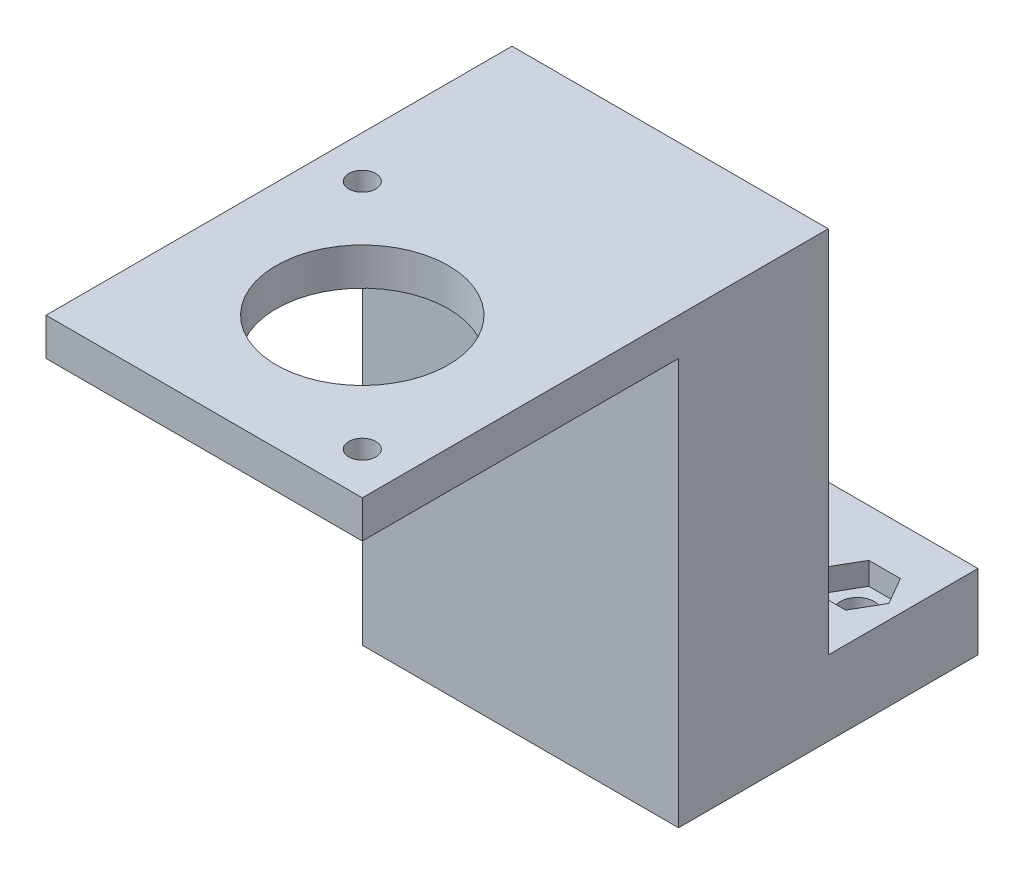
SolidWorks part; units mm, degrees
ref_plane "Front Plane" through (0, 0, 0) normal (0, 0, 1) x (1, 0, 0)
ref_plane "Top Plane" through (0, 0, 0) normal (0, 1, 0) x (1, 0, 0)
ref_plane "Right Plane" through (0, 0, 0) normal (1, 0, 0) x (0, 0, -1)
sketch "Sketch1" plane through (0, 0, 0) normal (1, 0, 0) x (0, 0, -1)
  line L0 (0, 0) -> (40, 0)
  line L1 (40, 0) -> (40, 10)
  line L2 (40, 10) -> (20, 10)
  line L3 (20, 10) -> (20, 59.3)
  line L4 (20, 59.3) -> (-42.25, 59.3)
  line L5 (-42.25, 59.3) -> (-42.25, 54.3)
  line L6 (-42.25, 54.3) -> (0, 54.3)
  line L7 (0, 0) -> (0, 54.3)
  dimension "D1" = 5
  dimension "D2" = 54.3
  dimension "D3" = 20
  dimension "D4" = 40
  dimension "D5" = 10
  dimension "D6" = 42.25
extrude "Boss-Extrude1" add sketch "Sketch1" along normal blind 42.25
sketch "Sketch3" plane through (0, 10, 0) normal (0, 1, 0) x (1, 0, 0)
  line L0 (21.125, 40) -> (21.125, 30.1909) construction
  line L1 (42.25, 40) -> (0, 40) construction
  circle A0 centre (6.125, 30) radius 2.25
  circle A1 centre (36.125, 30) radius 2.25
  dimension "D3" = 4.5
  dimension "D1" = 30
  dimension "D2" = 15
  dimension "D4" = 10
extrude "Cut-Extrude1" cut sketch "Sketch3" against normal through all
sketch "Sketch4" plane through (0, 54.3, 0) normal (0, -1, 0) x (1, 0, 0)
  line L0 (0, 21.125) -> (21.125, 21.125) construction
  line L1 (0, 42.25) -> (0, 0) construction
  line L2 (21.125, 42.25) -> (21.125, 21.125) construction
  line L3 (42.25, 42.25) -> (0, 42.25) construction
  circle A0 centre (21.125, 21.125) radius 11.5
  circle A1 centre (5.625, 5.625) radius 1.8
  circle A2 centre (36.625, 36.625) radius 1.8
  point P12 (5.625, 36.625)
  dimension "D1" = 23
  dimension "D6" = 3.6
  dimension "D2" = 31
  dimension "D3" = 15.5
  dimension "D4" = 31
  dimension "D5" = 15.5
extrude "Cut-Extrude2" cut sketch "Sketch4" against normal through all
sketch "Sketch5" plane through (0, 0, -20) normal (0, 0, -1) x (-1, 0, 0)
  line L0 (-21.125, 10) -> (-21.125, 33.8247) construction
  line L1 (-42.25, 10) -> (0, 10) construction
  circle A0 centre (-21.125, 43.6) radius 1.75
  circle A1 centre (-21.125, 37.6) radius 1.75
  dimension "D2" = 3.5
  dimension "D1" = 6
  dimension "D3" = 27.6
extrude "Cut-Extrude3" cut sketch "Sketch5" against normal through all
sketch "Sketch6" plane through (0, 0, 0) normal (0, 0, 1) x (1, 0, 0)
  line L0 (19.5084, 40.8) -> (19.5084, 40.4)
  line L1 (24.3582, 43.6) -> (22.7416, 46.4)
  line L2 (22.7416, 46.4) -> (19.5084, 46.4)
  line L3 (19.5084, 46.4) -> (17.8918, 43.6)
  line L4 (17.8918, 43.6) -> (19.5084, 40.8)
  line L6 (22.7416, 40.8) -> (24.3582, 43.6)
  line L7 (24.3582, 37.6) -> (22.7416, 40.4)
  line L9 (19.5084, 40.4) -> (17.8918, 37.6)
  line L10 (17.8918, 37.6) -> (19.5084, 34.8)
  line L11 (19.5084, 34.8) -> (22.7416, 34.8)
  line L12 (22.7416, 34.8) -> (24.3582, 37.6)
  line L13 (22.7416, 40.8) -> (22.7416, 40.4)
  line L15 (21.125, 40.8) -> (22.7416, 40.8) [skipped]
  line L16 (21.125, 40.4) -> (19.5084, 40.4) [skipped]
  circle A0 centre (21.125, 43.6) radius 2.8 construction
  circle A1 centre (21.125, 37.6) radius 2.8 construction
  circle A2 centre (21.125, 37.6) radius 1.75 construction
  circle A3 centre (21.125, 43.6) radius 1.75 construction
  dimension "D1" = 5.6
  dimension "D2" = 0.4
  dimension "D3" = 3.2332
extrude "Cut-Extrude4" cut sketch "Sketch6" against normal blind 5
sketch "Sketch7" plane through (0, 10, 0) normal (0, 1, 0) x (1, 0, 0)
  line L1 (10.3397, 30) -> (8.2323, 33.65)
  line L2 (8.2323, 33.65) -> (4.0177, 33.65)
  line L3 (4.0177, 33.65) -> (1.9103, 30)
  line L4 (1.9103, 30) -> (4.0177, 26.35)
  line L5 (4.0177, 26.35) -> (8.2323, 26.35)
  line L6 (8.2323, 26.35) -> (10.3397, 30)
  line L7 (40.3397, 30) -> (38.2323, 33.65)
  line L8 (38.2323, 33.65) -> (34.0177, 33.65)
  line L9 (34.0177, 33.65) -> (31.9103, 30)
  line L10 (31.9103, 30) -> (34.0177, 26.35)
  line L11 (34.0177, 26.35) -> (38.2323, 26.35)
  line L12 (38.2323, 26.35) -> (40.3397, 30)
  circle A0 centre (6.125, 30) radius 3.65 construction
  circle A1 centre (36.125, 30) radius 3.65 construction
  point P10 (0, 0)
  point P19 (0, 0)
  dimension "D1" = 7.3
extrude "Cut-Extrude5" cut sketch "Sketch7" against normal blind 3
